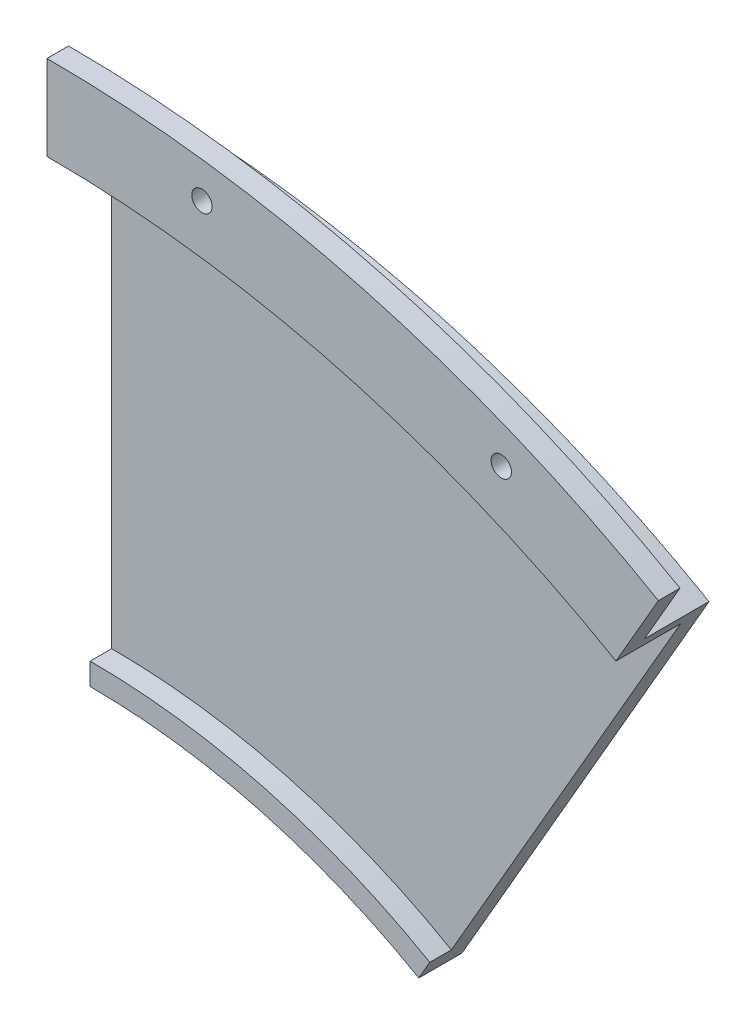
SolidWorks part; units mm, degrees
ref_plane "Front Plane" through (0, 0, 0) normal (0, 0, 1) x (1, 0, 0)
ref_plane "Top Plane" through (0, 0, 0) normal (0, 1, 0) x (1, 0, 0)
ref_plane "Right Plane" through (0, 0, 0) normal (1, 0, 0) x (0, 0, -1)
sketch "Sketch1" plane through (0, 0, 0) normal (0, 0, 1) x (1, 0, 0)
  line L0 (0, 0) -> (0, 242.4208) construction
  line L1 (0, 0) -> (129.5163, 224.3289) construction
  line L2 (48.3783, 83.7937) -> (90, 155.8846)
  line L3 (0, 96.7567) -> (0, 180)
  circle A0 centre (0, 0) radius 97 construction
  circle A1 centre (0, 0) radius 167.5 construction
  circle A2 centre (0, 0) radius 180 construction
  arc A3 (0, 96.7567) -> (48.3783, 83.7937) centre (0, 0) cw
  arc A4 (90, 155.8846) -> (0, 180) centre (0, 0) ccw
  dimension "D1" = 194
  dimension "D2" = 335
  dimension "D4" = 360
  dimension "D3" = 30
extrude "Boss-Extrude1" add sketch "Sketch1" along normal blind 12.7
sketch "Sketch2" plane through (0, 0, 12.7) normal (0, 0, 1) x (1, 0, 0)
  line L0 (0, 100) -> (0, 167.5)
  line L1 (50, 86.6025) -> (83.75, 145.0593)
  line L2 (48.3783, 83.7937) -> (90, 155.8846) construction
  arc A0 (50, 86.6025) -> (0, 100) centre (0, 0) ccw
  arc A1 (83.75, 145.0593) -> (0, 167.5) centre (0, 0) ccw
  dimension "D1" = 200
  dimension "D2" = 335
extrude "Cut-Extrude1" cut sketch "Sketch2" against normal blind 9.525
sketch "Sketch3" plane through (0, 0, 12.7) normal (0, 0, 1) x (1, 0, 0)
  line L0 (48.3783, 83.7937) -> (50, 86.6025)
  line L1 (0, 96.7567) -> (0, 100)
  arc A0 (48.3783, 83.7937) -> (0, 96.7567) centre (0, 0) ccw
  arc A1 (50, 86.6025) -> (0, 100) centre (0, 0) ccw
extrude "Cut-Extrude2" cut sketch "Sketch3" against normal blind 6.35
sketch "Sketch4" plane through (0, 0, 0) normal (0, 0, -1) x (-1, 0, 0)
  line L0 (0, 169.5) -> (0, 180)
  line L1 (-84.75, 146.7913) -> (-90, 155.8846)
  line L2 (-48.3783, 83.7937) -> (-90, 155.8846) construction
  arc A0 (0, 169.5) -> (-84.75, 146.7913) centre (0, 0) ccw
  arc A1 (0, 180) -> (-90, 155.8846) centre (0, 0) ccw
  dimension "D1" = 339
extrude "Cut-Extrude3" cut sketch "Sketch4" against normal blind 9.525
sketch "Sketch5" plane through (0, 0, 9.525) normal (0, 0, -1) x (-1, 0, 0)
  line L0 (0, 0) -> (0, 226.9347) construction
  line L1 (0, 0) -> (-60.6799, 226.4605) construction
  line L2 (0, 0) -> (-30.5402, 231.9758) construction
  circle A0 centre (0, 0) radius 174.75 construction
  circle A2 centre (-22.8095, 173.255) radius 1.5
  circle A3 centre (-66.8739, 161.4479) radius 1.5
  dimension "D3" = 349.5
  dimension "D4" = 3
  dimension "D1" = 15
  dimension "D2" = 7.5
extrude "Cut-Extrude4" cut sketch "Sketch5" against normal blind 3.175
